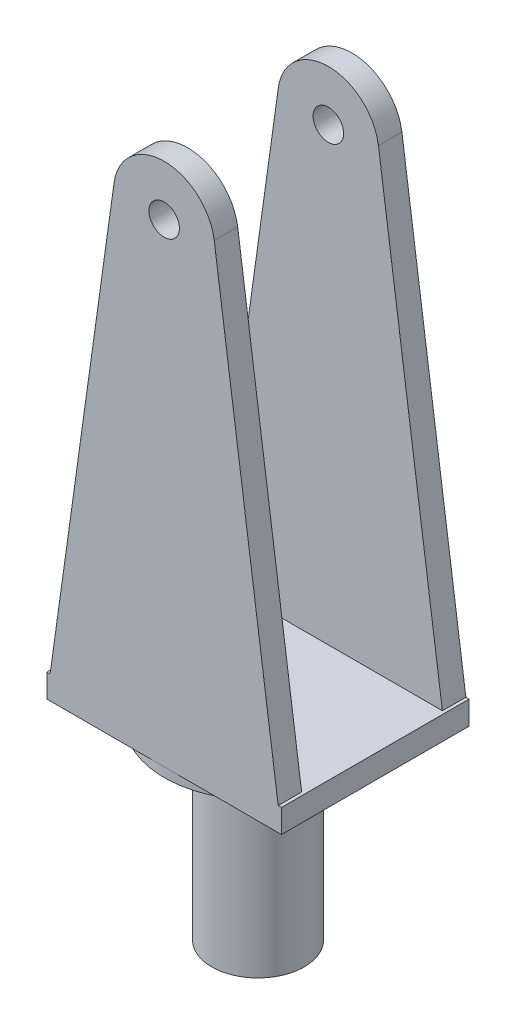
SolidWorks part; units mm, degrees
material "PBT General Purpose"
ref_plane "Front Plane" through (0, 0, 0) normal (0, 0, 1) x (1, 0, 0)
ref_plane "Top Plane" through (0, 0, 0) normal (0, 1, 0) x (1, 0, 0)
ref_plane "Right Plane" through (0, 0, 0) normal (1, 0, 0) x (0, 0, -1)
sketch "Sketch1" plane through (0, 0, 0) normal (0, 1, 0) x (1, 0, 0)
  line L1 (-12.5, -10) -> (12.5, -10)
  line L2 (-12.5, -10) -> (-12.5, 10)
  line L3 (-12.5, 10) -> (12.5, 10)
  line L4 (12.5, -10) -> (12.5, 10)
  line L5 (-12.5, -10) -> (12.5, 10) construction
  line L6 (-12.5, 10) -> (12.5, -10) construction
  point P0 (0, 0)
  dimension "D1" = 20
  dimension "D2" = 25
extrude "Boss-Extrude1" add sketch "Sketch1" along normal blind 2.5
ref_plane "Plane1" through (0, 0, 0) normal (0, 0, -1) x (-1, 0, 0)
sketch "Sketch4" plane through (0, 0, 0) normal (0, -1, 0) x (1, 0, 0)
  line L0 (12.5, -10) -> (-12.5, -10) construction
  circle A0 centre (0, 0) radius 10
extrude "Boss-Extrude3" add sketch "Sketch4" along normal blind 1
sketch "Sketch5" plane through (0, -1, 0) normal (0, -1, 0) x (1, 0, 0)
  circle A0 centre (0, 0) radius 4.9365
  dimension "D1" = 9.873
extrude "Boss-Extrude4" add sketch "Sketch5" along normal blind 20
sketch "Sketch6" plane through (0, 0, -10) normal (0, 0, -1) x (-1, 0, 0)
  line L1 (12.5, 0) -> (-12.5, 0)
  line L2 (12.5, 0) -> (5.3349, 51.2454)
  line L5 (-10, -1) -> (10, -1) construction
  line L6 (-10, -1) -> (10, -1)
  line L7 (0, -1) -> (0, 50.5) construction
  line L8 (-12.5, 0) -> (-5.3349, 51.2454)
  line L9 (0, 52.127) -> (0, 55.8867) construction
  circle A0 centre (0, 50.5) radius 1.627
  arc A1 (5.3349, 51.2454) -> (-5.3349, 51.2454) centre (0, 50.5) ccw
  point P6 (-4.9978, 0)
  point P13 (0, 0)
  dimension "D2" = 3.254
  dimension "D1" = 51.5
  dimension "D3" = 3.7597
extrude "Boss-Extrude5" add sketch "Sketch6" against normal blind 2.5
mirror "Mirror2" about plane through (0, 0, 0) normal (0, 0, -1) of "Boss-Extrude5"
